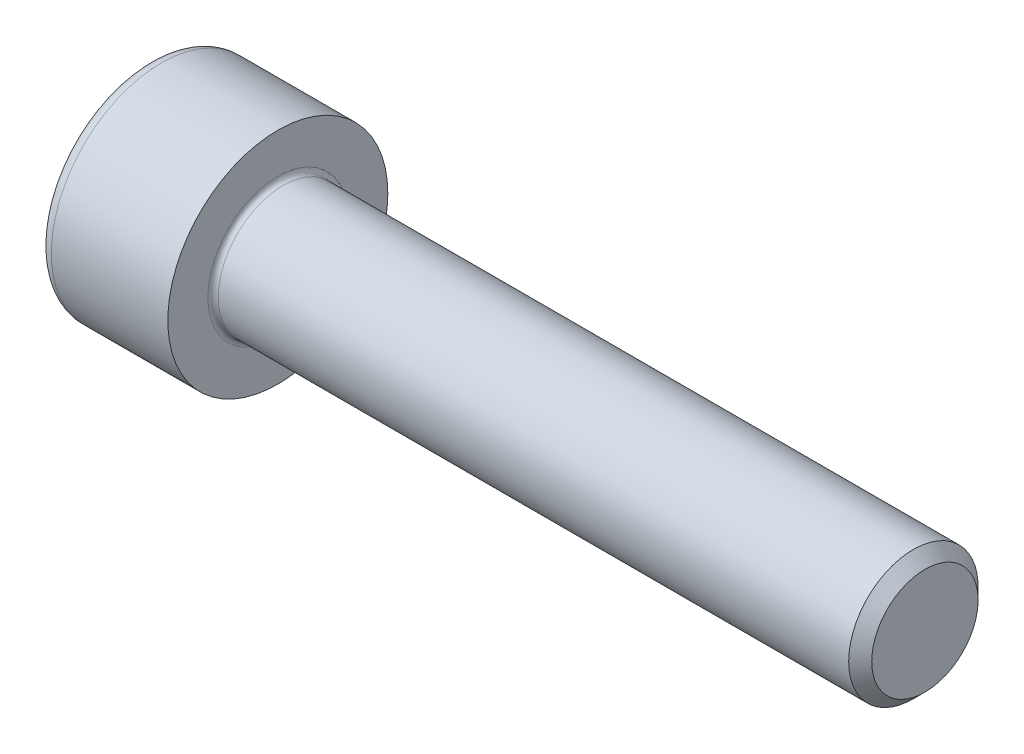
SolidWorks part; units mm, degrees
ref_plane "Front Plane" through (0, 0, 0) normal (0, 0, 1) x (1, 0, 0)
ref_plane "Top Plane" through (0, 0, 0) normal (0, 1, 0) x (1, 0, 0)
ref_plane "Right Plane" through (0, 0, 0) normal (1, 0, 0) x (0, 0, -1)
other "Configuration Table"
sketch "BaseHeadSke" plane through (0, 0, 0) normal (1, 0, 0) x (0, 0, -1)
  circle A1 centre (0, 0) radius 4.25
  dimension "Head_diameter" = 8.5
extrude "BaseHead" add sketch "BaseHeadSke" along normal blind 5
sketch "BodySke" plane through (0, 0, 0) normal (0, 0, 1) x (1, 0, 0)
  line L0 (0, 0) -> (30, 0)
  line L1 (30, 0) -> (30, 2.055)
  line L2 (30, 2.055) -> (29.555, 2.5)
  line L3 (29.555, 2.5) -> (0, 2.5)
  line L4 (0, 2.5) -> (0, 0)
  line L6 (0, 0) -> (159.3976, 0) construction
  line L7 (5, -84.3176) -> (5, 77.7215) construction
  line L8 (29.2, -21.5941) -> (29.2, 39.2994) construction
  line L10 (5, -4.25) -> (5, 4.25) construction
  dimension "Ang" = 45
  dimension "Diameter" = 5
  dimension "Minor_dia" = 4.11
  dimension "Thread_length" = 25
  dimension "Advance" = 0.8
  dimension "Length" = 25
revolve "BaseBody" add sketch "BodySke" angle 360 about L6
cosmetic thread "ThreadCosmetic" [suppressed] parameters "Thread_length"=25, "Thread_minor"=4.11
sketch "CutSocketSke" plane through (0, 0, 0) normal (1, 0, 0) x (0, 0, -1)
  line L1 (0, 2.3094) -> (-2, 1.1547)
  line L2 (-2, 1.1547) -> (-2, -1.1547)
  line L3 (-2, -1.1547) -> (0, -2.3094)
  line L4 (0, -2.3094) -> (2, -1.1547)
  line L5 (2, -1.1547) -> (2, 1.1547)
  line L6 (2, 1.1547) -> (0, 2.3094)
  circle A0 centre (0, 0) radius 2 construction
  dimension "Socket_width" = 4
extrude "CutSocket" cut sketch "CutSocketSke" along normal blind 2.5
sketch "CutHoleSke" plane through (0, 0, 0) normal (0, 0, 1) x (1, 0, 0)
  line L0 (0, 0) -> (149.4323, 0) construction
  line L1 (0, 2) -> (3.1, 2)
  line L2 (3.1, 2) -> (4.2547, 0)
  line L3 (4.2547, 0) -> (0, 0)
  line L4 (0, 0) -> (0, 2)
  line L6 (5, -4.25) -> (5, 4.25) construction
  dimension "D1" = 60
  dimension "Hole_depth" = 1.9
  dimension "D2" = 4
revolve "CutHole" cut sketch "CutHoleSke" angle 360 about L0
fillet "Fillet1" radius 0.2 1 edges at (5, 0, -2.5)
fillet "Fillet2" radius 0.5 1 edges at (0, 0, -4.25)
sketch "ThdSchSke" plane through (0, 0, 0) normal (0, 0, 1) x (1, 0, 0)
  line L0 (28.9431, 3.0138) -> (28.9431, 2.5)
  line L1 (28.9431, 2.5) -> (29.2, 2.055)
  line L2 (29.2, 2.055) -> (29.4569, 2.5)
  line L3 (29.4569, 2.5) -> (29.4569, 3.0138)
  line L4 (29.4569, 3.0138) -> (28.9431, 3.0138)
  line L6 (0, 0) -> (141.9934, 0) construction
  line L7 (30, -2.055) -> (30, 2.055) construction
  dimension "Advance" = 0.8
  dimension "D2" = 4.11
  dimension "D3" = 5
revolve "ThreadSchematic" [suppressed] cut sketch "ThdSchSke" angle 360 about L6
pattern_linear "ThdSchPat" [suppressed] count 30 spacing 0.8 along (1, 0, 0)
equation "\"Thread_minor@ThreadCosmetic\" = \"Minor_dia@BodySke\""
equation "\"Thread_length@ThreadCosmetic\" = \"Thread_length@BodySke\""
equation "\"D2@CutHoleSke\" = \"Socket_width@CutSocketSke\""
equation "\"D2@ThdSchSke\" = \"Minor_dia@BodySke\""
equation "\"D3@ThdSchSke\" = \"Diameter@BodySke\""
equation "\"Advance@ThdSchSke\" = \"Advance@BodySke\""
equation "\"D3@ThdSchPat\" = \"Advance@BodySke\""
equation "\"D1@ThdSchPat\" =  int( \"Thread_length@BodySke\"/\"Advance@BodySke\" )-1"
